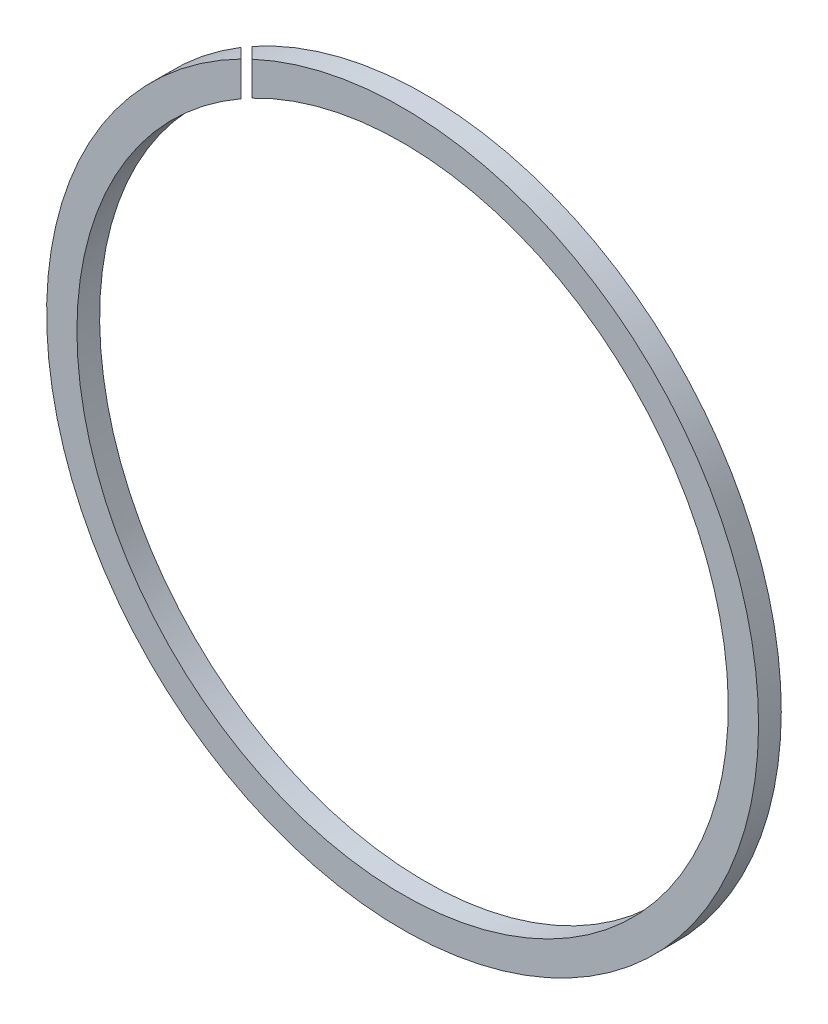
SolidWorks part; units mm, degrees
ref_plane "Front Plane" through (0, 0, 0) normal (1, 0, 0) x (0, 1, 0)
ref_plane "Top Plane" through (0, 0, 0) normal (0, 0, 1) x (0, 1, 0)
ref_plane "Right Plane" through (0, 0, 0) normal (0, 1, 0) x (-1, 0, 0)
sketch "Sketch1" plane through (0, 0, 0) normal (0, 0, 1) x (0, 1, 0)
  line L0 (0, 0) -> (81.4524, 0) construction
  circle A0 centre (0, 0) radius 47
  circle A1 centre (0, 0) radius 43
  dimension "D1" = 94
  dimension "D2" = 86
extrude "Boss-Extrude1" add sketch "Sketch1" along normal mid plane 3
sketch "Sketch4" plane through (0, 0, 0) normal (0, 1, 0) x (-1, 0, 0)
  line L0 (0, 32.1843) -> (0, -27.6959) construction
  line L1 (0, 22.1161) -> (45.3717, -23.2556) construction
  line L2 (19.909, 1.5) -> (22.909, -1.5)
  line L3 (47, 1.5) -> (-47, 1.5) construction
  line L4 (-47, -1.5) -> (47, -1.5) construction
  line L5 (21.3232, 1.5) -> (24.3232, -1.5)
  line L6 (19.909, 1.5) -> (21.3232, 1.5)
  line L7 (24.3232, -1.5) -> (22.909, -1.5)
  dimension "D1" = 64.1653
  dimension "D2" = 135
  dimension "D3" = 1
extrude "Cut-Extrude1" cut sketch "Sketch4" along normal blind 100
